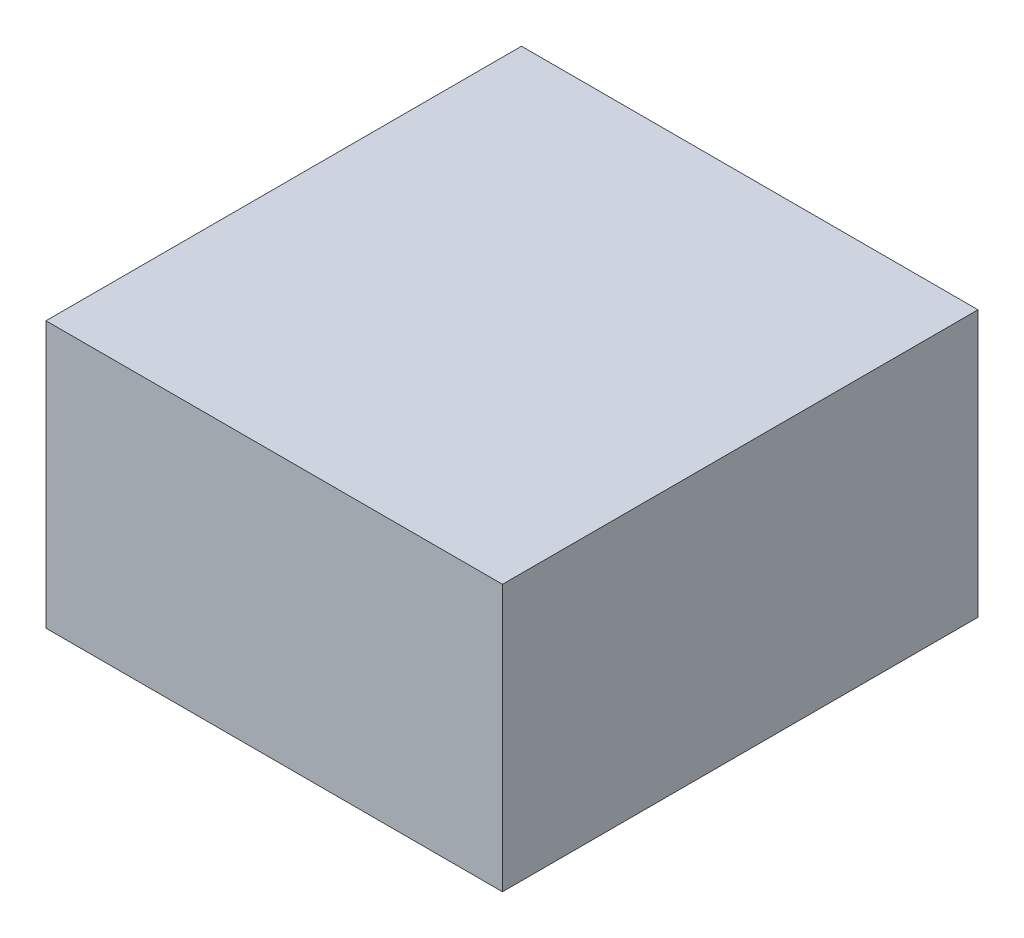
SolidWorks part; units mm, degrees
ref_plane "Alzado" through (0, 0, 0) normal (0, 0, 1) x (1, 0, 0)
ref_plane "Planta" through (0, 0, 0) normal (0, 1, 0) x (1, 0, 0)
ref_plane "Vista lateral" through (0, 0, 0) normal (1, 0, 0) x (0, 0, -1)
sketch "Croquis1" plane through (0, 0, 0) normal (0, 0, 1) x (1, 0, 0)
  line L1 (-24, 14) -> (24, 14)
  line L2 (-24, 14) -> (-24, -14)
  line L3 (-24, -14) -> (24, -14)
  line L4 (24, 14) -> (24, -14)
  line L5 (-24, 14) -> (24, -14) construction
  line L6 (-24, -14) -> (24, 14) construction
  point P0 (0, 0)
  dimension "D1" = 48
  dimension "D2" = 28
extrude "Saliente-Extruir1" add sketch "Croquis1" along normal blind 50
sketch "Croquis2" plane through (0, 0, 0) normal (0, 0, 1) x (1, 0, 0)
  circle A0 centre (0, 0) radius 5
  dimension "D1" = 10
extrude "Cortar-Extruir1" cut sketch "Croquis2" along normal blind 10
